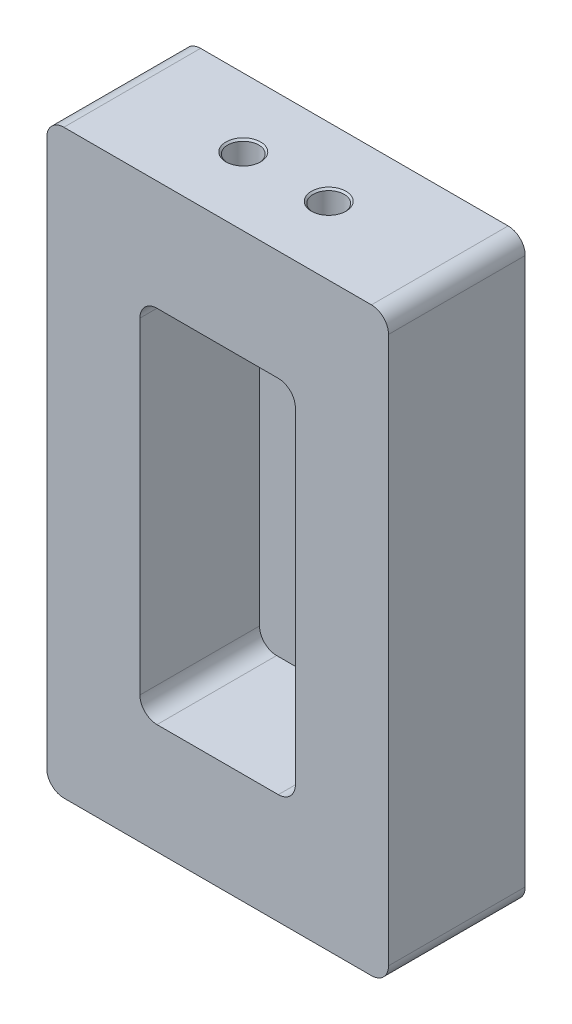
SolidWorks part; units mm, degrees
ref_plane "Front Plane" through (0, 0, 0) normal (0, 0, 1) x (1, 0, 0)
ref_plane "Top Plane" through (0, 0, 0) normal (0, 1, 0) x (1, 0, 0)
ref_plane "Right Plane" through (0, 0, 0) normal (1, 0, 0) x (0, 0, -1)
sketch "Sketch1" plane through (0, 0, 0) normal (0, 0, 1) x (1, 0, 0)
  line L1 (0, 0) -> (100, 0)
  line L2 (0, 0) -> (0, 170)
  line L3 (0, 170) -> (100, 170)
  line L4 (100, 0) -> (100, 170)
  dimension "D1" = 170
  dimension "D2" = 100
extrude "Boss-Extrude1" add sketch "Sketch1" along normal blind 40
hole_wizard "1/8-27 NPSM Tapped Hole1" positions "Sketch3" profile "Sketch5" tap size "1/8-27 NPSM" standard "ANSI Metric"
sketch "Sketch3" plane through (0, 170, 0) normal (0, 1, 0) x (1, 0, 0)
  line L0 (62.5, -20) -> (37.5, -20) construction
  line L3 (100, -40) -> (0, -40) construction
  point P0 (37.5, -20)
  point P2 (62.5, -20)
  point P9 (50, -20)
  point P12 (50, -40)
  dimension "D1" = 25
  dimension "D2" = 20
sketch "Sketch5" plane through (37.5, 170, 20) normal (1, 0, 0) x (0, 0, 1)
  line L0 (0, 0) -> (0, 25.7189)
  line L1 (0, 25.7189) -> (4.5466, 22.987)
  line L2 (4.5466, 22.987) -> (4.5466, 0.5203)
  line L3 (4.5466, 0.5203) -> (5.0669, 0)
  line L5 (5.0669, 0) -> (0, 0)
  line L6 (-4.5466, 0.5203) -> (-5.0669, 0) construction
  line L10 (0, 25.7189) -> (-4.5466, 22.987) construction
  line L11 (0, -6.35) -> (0, 107.95) construction
  dimension "Tap Drill Dia." = 9.0932
  dimension "Tap Drill Depth" = 22.987
  dimension "Near C'Sink Dia." = 10.1338
  dimension "Near C'Sink Angle" = 90
  dimension "Drill Angle" = 118
cosmetic thread "Hole Thread1" parameters "D1"=10, "D2"=10.0838
cosmetic thread "Hole Thread2" parameters "D1"=10, "D2"=10.0838
sketch "Sketch10" plane through (0, 170, 0) normal (0, 1, 0) x (1, 0, 0)
  point P0 (62.5, -20)
  point P1 (37.5, -20)
sketch "Sketch11" plane through (0, 0, 40) normal (0, 0, 1) x (1, 0, 0)
  line L0 (0, 0) -> (100, 0) construction
  line L1 (27.25, 137.75) -> (72.75, 137.75)
  line L2 (27.25, 137.75) -> (27.25, 32.25)
  line L3 (27.25, 32.25) -> (72.75, 32.25)
  line L4 (72.75, 137.75) -> (72.75, 32.25)
  line L6 (100, 170) -> (0, 170) construction
  point P4 (50, 32.25)
  point P7 (50, 0)
  dimension "D1" = 45.5
  dimension "D2" = 105.5
  dimension "D3" = 32.25
extrude "Cut-Extrude3" cut sketch "Sketch11" against normal blind 35
sketch "Sketch12" plane through (0, 0, 0) normal (0, 0, -1) x (-1, 0, 0)
  line L0 (-100, 0) -> (-100, 170) construction
  line L1 (-90, 160) -> (-75, 160)
  line L2 (-90, 160) -> (-90, 10)
  line L3 (-90, 10) -> (-75, 10)
  line L4 (-75, 160) -> (-75, 25)
  line L5 (0, 0) -> (-100, 0) construction
  line L6 (-100, 170) -> (0, 170) construction
  line L7 (0, 170) -> (0, 0) construction
  line L8 (-75, 10) -> (-25, 10)
  line L10 (-75, 25) -> (-25, 25)
  line L12 (-25, 160) -> (-10, 160)
  line L13 (-25, 160) -> (-25, 25)
  line L14 (-25, 10) -> (-10, 10)
  line L15 (-10, 160) -> (-10, 10)
  dimension "D1" = 10
  dimension "D2" = 10
  dimension "D3" = 10
  dimension "D4" = 15
  dimension "D5" = 15
  dimension "D6" = 10
  dimension "D7" = 10
  dimension "D8" = 15
extrude "Cut-Extrude4" cut sketch "Sketch12" against normal blind 35
sketch "Sketch13" plane through (0, 0, 0) normal (0, 0, -1) x (-1, 0, 0)
  line L1 (-75, 160) -> (-52.5, 160)
  line L2 (-75, 160) -> (-75, 145)
  line L3 (-75, 145) -> (-52.5, 145)
  line L4 (-52.5, 160) -> (-52.5, 145)
  line L5 (-25, 160) -> (-47.5, 160)
  line L6 (-25, 160) -> (-25, 145)
  line L7 (-25, 145) -> (-47.5, 145)
  line L8 (-47.5, 160) -> (-47.5, 145)
  dimension "D1" = 15
  dimension "D2" = 15
  dimension "D3" = 5
extrude "Cut-Extrude5" cut sketch "Sketch13" against normal blind 35
fillet "Fillet1" radius 5 12 edges at (10, 10, 17.5) (25, 25, 17.5) (75, 25, 17.5) (90, 10, 17.5) (90, 160, 17.5) (10, 160, 17.5) (25, 145, 17.5) (47.5, 145, 17.5) (47.5, 160, 17.5) (52.5, 160, 17.5) (52.5, 145, 17.5) (75, 145, 17.5)
fillet "Fillet2" radius 5 4 edges at (27.25, 137.75, 22.5) (72.75, 137.75, 22.5) (72.75, 32.25, 22.5) (27.25, 32.25, 22.5)
hole_wizard "M3x0.5 Tapped Hole1" positions "Sketch14" profile "Sketch15" tap size "M3x0.5" standard "ANSI Metric"
sketch "Sketch14" plane through (0, 0, 0) normal (0, 0, -1) x (-1, 0, 0)
  line L0 (-100, 170) -> (0, 170) construction
  line L1 (-100, 0) -> (-100, 170) construction
  line L2 (0, 170) -> (0, 0) construction
  line L3 (0, 0) -> (-100, 0) construction
  point P0 (-95, 165)
  point P2 (-50, 165)
  point P4 (-5, 165)
  point P6 (-5, 85)
  point P8 (-5, 5)
  point P10 (-50, 5)
  point P12 (-95, 5)
  point P14 (-95, 85)
  point P25 (-100, 85)
  point P26 (-50, 0)
  dimension "D1" = 5
  dimension "D2" = 5
  dimension "D3" = 5
  dimension "D4" = 5
  dimension "D5" = 5
  dimension "D6" = 5
  dimension "D7" = 5
  dimension "D8" = 5
  dimension "D9" = 5
  dimension "D10" = 5
  dimension "D11" = 5
  dimension "D12" = 5
sketch "Sketch15" plane through (95, 165, 0) normal (1, 0, 0) x (0, 1, 0)
  line L0 (0, 0) -> (0, 8.2511)
  line L1 (0, 8.2511) -> (1.25, 7.5)
  line L2 (1.25, 7.5) -> (1.25, 0.275)
  line L3 (1.25, 0.275) -> (1.525, 0)
  line L5 (1.525, 0) -> (0, 0)
  line L6 (-1.25, 0.275) -> (-1.525, 0) construction
  line L10 (0, 8.2511) -> (-1.25, 7.5) construction
  line L11 (0, -6.35) -> (0, 107.95) construction
  dimension "Tap Drill Dia." = 2.5
  dimension "Tap Drill Depth" = 7.5
  dimension "Near C'Sink Dia." = 3.05
  dimension "Near C'Sink Angle" = 90
  dimension "Drill Angle" = 118
cosmetic thread "Hole Thread3" parameters "D1"=6, "D2"=3
cosmetic thread "Hole Thread4" parameters "D1"=6, "D2"=3
cosmetic thread "Hole Thread5" parameters "D1"=6, "D2"=3
cosmetic thread "Hole Thread6" parameters "D1"=6, "D2"=3
cosmetic thread "Hole Thread7" parameters "D1"=6, "D2"=3
cosmetic thread "Hole Thread8" parameters "D1"=6, "D2"=3
cosmetic thread "Hole Thread9" parameters "D1"=6, "D2"=3
cosmetic thread "Hole Thread10" parameters "D1"=6, "D2"=3
fillet "Fillet3" radius 5 4 edges at (0, 0, 20) (100, 0, 20) (100, 170, 20) (0, 170, 20)
